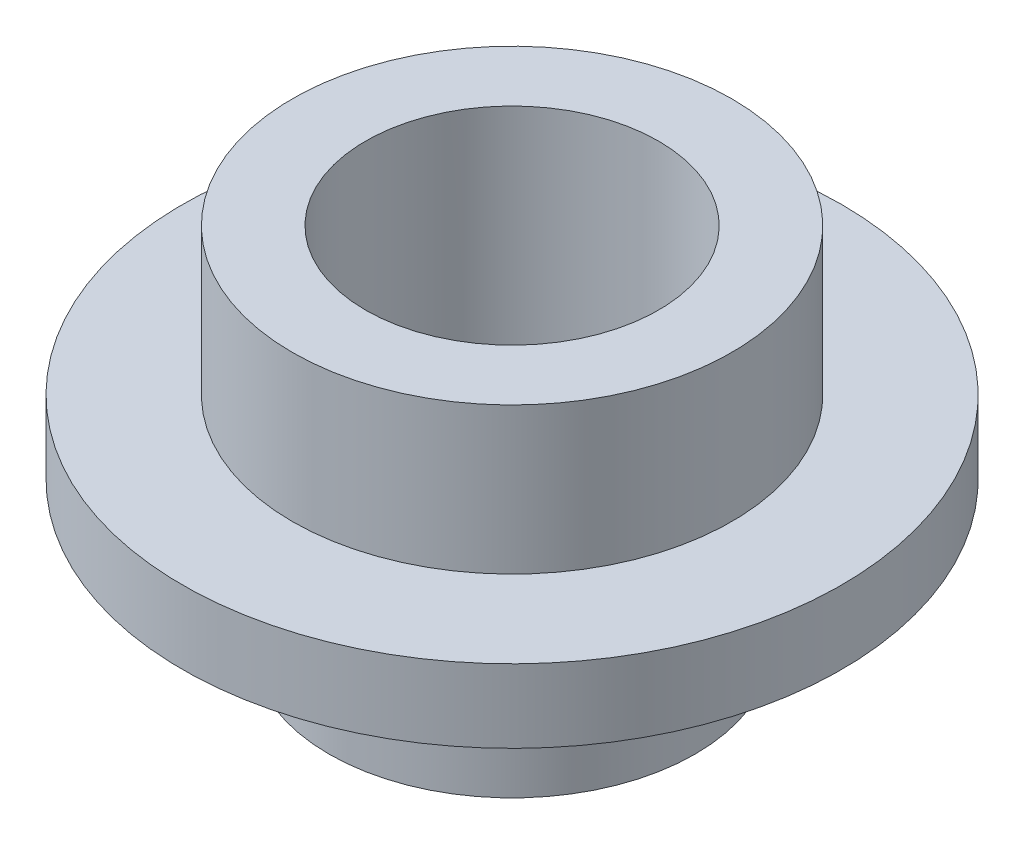
SolidWorks part; units mm, degrees
ref_plane "Front Plane" through (0, 0, 0) normal (0, 0, 1) x (1, 0, 0)
ref_plane "Top Plane" through (0, 0, 0) normal (0, 1, 0) x (1, 0, 0)
ref_plane "Right Plane" through (0, 0, 0) normal (1, 0, 0) x (0, 0, -1)
sketch "Sketch1" plane through (0, 0, 0) normal (0, 1, 0) x (1, 0, 0)
  circle A0 centre (0, 0) radius 19.05
  circle A1 centre (0, 0) radius 12.7
  dimension "D1" = 38.1
  dimension "D2" = 25.4
extrude "Top" add sketch "Sketch1" along normal blind 12.7
sketch "Sketch4" plane through (0, 0, 0) normal (0, -1, 0) x (1, 0, 0)
  circle A0 centre (0, 0) radius 28.575
  circle A1 centre (0, 0) radius 12.7
  dimension "D1" = 57.15
  dimension "D2" = 25.4
extrude "Middle" add sketch "Sketch4" along normal blind 6.35
sketch "Sketch5" plane through (0, -6.35, 0) normal (0, -1, 0) x (1, 0, 0)
  circle A0 centre (0, 0) radius 12.7
  circle A1 centre (0, 0) radius 15.875
  dimension "D1" = 25.4
  dimension "D2" = 31.75
extrude "Bottom" add sketch "Sketch5" along normal blind 12.7
